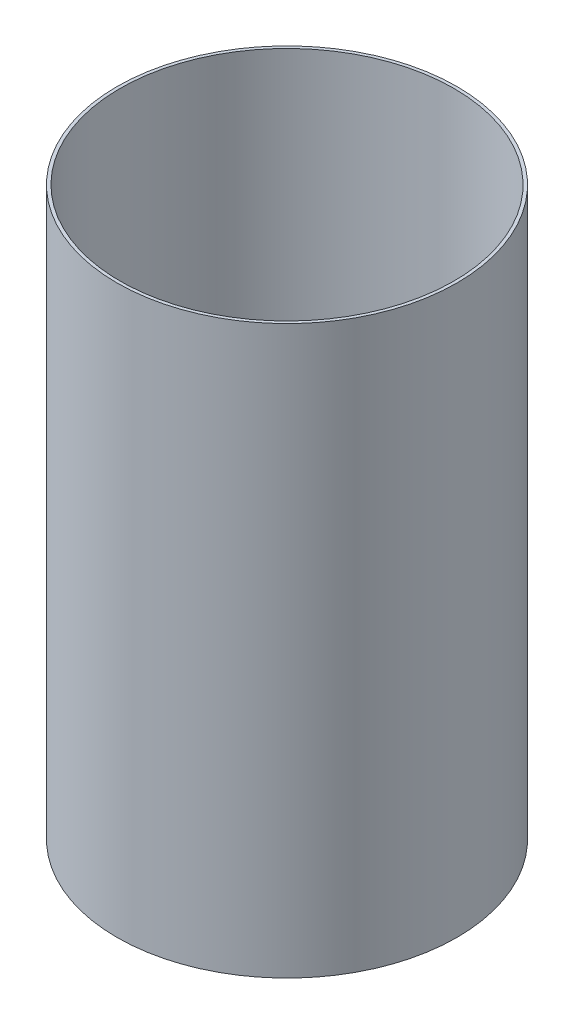
SolidWorks part; units mm, degrees
ref_plane "Front Plane" through (0, 0, 0) normal (0, 0, 1) x (1, 0, 0)
ref_plane "Top Plane" through (0, 0, 0) normal (0, 1, 0) x (1, 0, 0)
ref_plane "Right Plane" through (0, 0, 0) normal (1, 0, 0) x (0, 0, -1)
sketch "Sketch1" plane through (0, -290, 0) normal (0, -1, 0) x (-1, 0, 0)
  line L3 (-43.0706, -45.3156) -> (-46.7728, -49.0178)
  line L5 (-49.0178, -46.7728) -> (-45.3156, -43.0706)
  circle A0 centre (0, 0) radius 67.7342
  circle A1 centre (0, 0) radius 69.0042
  ellipse E0 centre (-47.8953, -47.8953) end of major axis (-46.7728, -49.0178) minor radius 1.5873 (-49.0178, -46.7728) -> (-46.7728, -49.0178) ccw
  ellipse E1 centre (-47.8953, -47.8953) end of major axis (-46.7728, -49.0178) minor radius 1.5873 (-49.0178, -46.7728) -> (-46.7728, -49.0178) ccw construction
  ellipse E2 centre (-44.1931, -44.1931) end of major axis (-43.0706, -45.3156) minor radius 1.5873 (-43.0706, -45.3156) -> (-45.3156, -43.0706) ccw
  point P6 (0, 0)
  dimension "D1" = 1.27
extrude "Boss-Extrude1" add sketch "Sketch1" against normal blind 230
